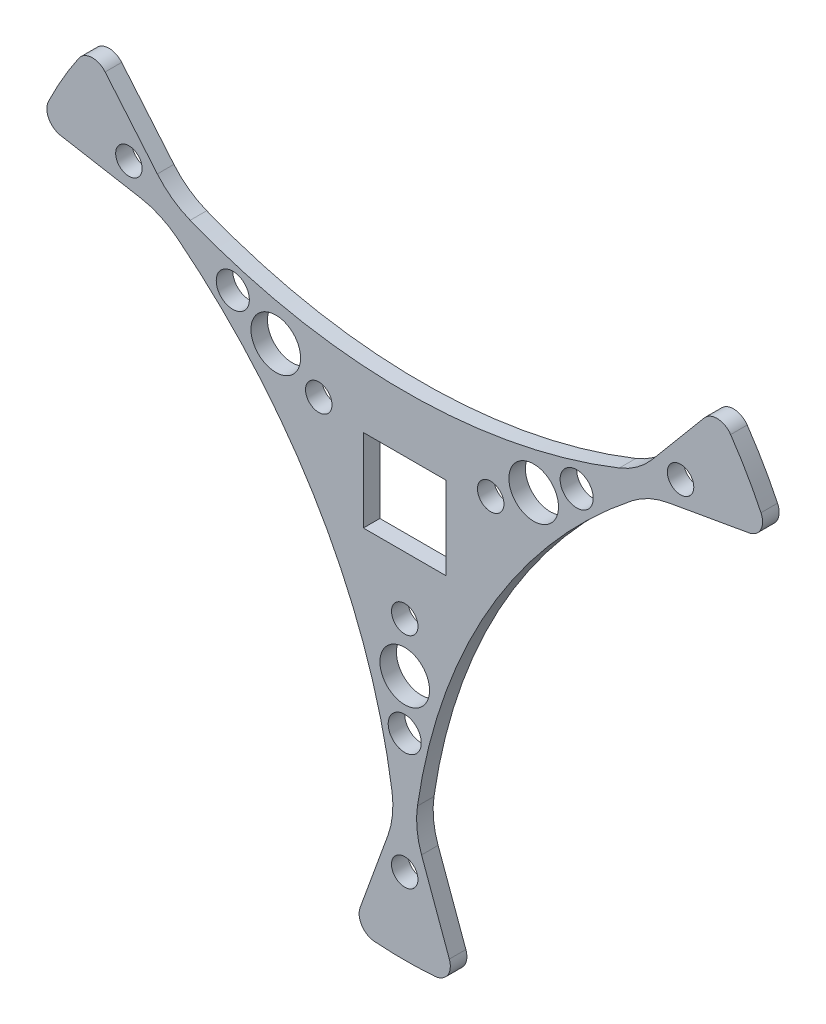
SolidWorks part; units mm, degrees
material "Thornel Mat VMA"
ref_plane "正面" through (0, 0, 0) normal (0, 0, 1) x (1, 0, 0)
ref_plane "平面" through (0, 0, 0) normal (0, 1, 0) x (1, 0, 0)
ref_plane "右側面" through (0, 0, 0) normal (1, 0, 0) x (0, 0, -1)
sketch "ｽｹｯﾁ1" plane through (0, 0, 0) normal (0, 0, 1) x (1, 0, 0)
  circle A0 centre (0, 0) radius 47.75
  dimension "D1" = 95.5
extrude "ﾎﾞｽ - 押し出し1" add sketch "ｽｹｯﾁ1" along normal blind 2
sketch "ｽｹｯﾁ2" plane through (0, 0, 2) normal (0, 0, 1) x (1, 0, 0)
  line L0 (-10.3, 46.6259) -> (-10.3, 31.8257) construction
  line L1 (10.3, 46.6259) -> (10.3, 31.8257) construction
  line L2 (0, 47.75) -> (0, -47.75) construction
  line L8 (22.0803, 42.3382) -> (12.5669, 31.0006) construction
  line L9 (37.8608, 29.0968) -> (28.3474, 17.7592) construction
  line L13 (0, 30.78) -> (0, 41.18) construction
  line L94 (44.1289, 18.24) -> (29.5536, 15.67) construction
  line L95 (47.7061, -2.047) -> (33.1308, -4.617) construction
  line L96 (45.5292, -14.3929) -> (32.7119, -6.9928) construction
  line L97 (35.2292, -32.233) -> (22.4119, -24.8329) construction
  line L98 (25.6258, -40.2912) -> (20.5639, -26.3836) construction
  line L99 (6.2682, -47.3368) -> (1.2062, -33.4292) construction
  line L100 (-6.2682, -47.3368) -> (-1.2062, -33.4292) construction
  line L101 (-25.6258, -40.2912) -> (-20.5639, -26.3836) construction
  line L102 (-35.2292, -32.233) -> (-22.4119, -24.8329) construction
  line L103 (-45.5292, -14.3929) -> (-32.7119, -6.9928) construction
  line L104 (-47.7061, -2.047) -> (-33.1308, -4.617) construction
  line L105 (-44.1289, 18.24) -> (-29.5536, 15.67) construction
  line L106 (-37.8608, 29.0968) -> (-28.3474, 17.7592) construction
  line L107 (-22.0803, 42.3382) -> (-12.5669, 31.0006) construction
  line L108 (-44.1289, 18.24) -> (-29.5536, 15.67)
  line L109 (-6.2682, -47.3368) -> (-1.2062, -33.4292)
  line L110 (6.2682, -47.3368) -> (1.2062, -33.4292)
  line L111 (29.5536, 15.67) -> (44.1289, 18.24)
  line L112 (-37.8608, 29.0968) -> (-28.3474, 17.7592)
  line L113 (28.3474, 17.7592) -> (37.8608, 29.0968)
  circle A0 centre (0, 0) radius 47.75 construction
  arc A1 (-10.3, 46.6259) -> (10.3, 46.6259) centre (0, 0) cw construction
  arc A2 (-10.3, 31.8257) -> (10.3, 31.8257) centre (0, 82.03) ccw construction
  arc A19 (12.5669, 31.0006) -> (28.3474, 17.7592) centre (52.7279, 62.8386) ccw construction
  arc A20 (22.0803, 42.3382) -> (37.8608, 29.0968) centre (0, 0) cw construction
  arc A21 (29.5536, 15.67) -> (33.1308, -4.617) centre (80.7838, 14.2444) ccw construction
  arc A22 (44.1289, 18.24) -> (47.7061, -2.047) centre (0, 0) cw construction
  arc A23 (32.7119, -6.9928) -> (22.4119, -24.8329) centre (71.0401, -41.015) ccw construction
  arc A24 (45.5292, -14.3929) -> (35.2292, -32.233) centre (0, 0) cw construction
  arc A25 (20.5639, -26.3836) -> (1.2062, -33.4292) centre (28.0559, -77.083) ccw construction
  arc A26 (25.6258, -40.2912) -> (6.2682, -47.3368) centre (0, 0) cw construction
  arc A27 (-1.2062, -33.4292) -> (-20.5639, -26.3836) centre (-28.0559, -77.083) ccw construction
  arc A28 (-6.2682, -47.3368) -> (-25.6258, -40.2912) centre (0, 0) cw construction
  arc A29 (-22.4119, -24.8329) -> (-32.7119, -6.9928) centre (-71.0401, -41.015) ccw construction
  arc A30 (-35.2292, -32.233) -> (-45.5292, -14.3929) centre (0, 0) cw construction
  arc A31 (-33.1308, -4.617) -> (-29.5536, 15.67) centre (-80.7838, 14.2444) ccw construction
  arc A32 (-47.7061, -2.047) -> (-44.1289, 18.24) centre (0, 0) cw construction
  arc A33 (-28.3474, 17.7592) -> (-12.5669, 31.0006) centre (-52.7279, 62.8386) ccw construction
  arc A34 (-37.8608, 29.0968) -> (-22.0803, 42.3382) centre (0, 0) cw construction
  arc A35 (-29.5536, 15.67) -> (-1.2062, -33.4292) centre (-71.0401, -41.015) cw
  arc A36 (1.2062, -33.4292) -> (29.5536, 15.67) centre (71.0401, -41.015) cw
  arc A37 (-44.1289, 18.24) -> (-6.2682, -47.3368) centre (0, 0) ccw
  arc A38 (6.2682, -47.3368) -> (44.1289, 18.24) centre (0, 0) ccw
  arc A39 (-28.3474, 17.7592) -> (28.3474, 17.7592) centre (0, 82.03) ccw
  arc A40 (-37.8608, 29.0968) -> (37.8608, 29.0968) centre (0, 0) cw
  circle A41 centre (0, -38.5) radius 1.6
  circle A42 centre (-33.342, 19.25) radius 1.6
  circle A44 centre (33.342, 19.25) radius 1.6
  point P11 (0, 41.18)
  point P56 (0, 0)
  point P67 (0, 0)
  point P139 (0, 0)
  dimension "D2" = 20.6
  dimension "D7" = 51.25
  dimension "D5" = 3.2
  dimension "D8" = 38.5
  dimension "D1" = 41.18
  dimension "D3" = 10.3
  dimension "D4" = 9
  dimension "D6" = 10.4
  dimension "D9" = 3
extrude "ｶｯﾄ - 押し出し1" cut sketch "ｽｹｯﾁ2" against normal through all
fillet "ﾌｨﾚｯﾄ1" radius 10 6 edges at (-1.2062, -33.4292, 1) (1.2062, -33.4292, 1) (29.5536, 15.67, 1) (28.3474, 17.7592, 1) (-28.3474, 17.7592, 1) (-29.5536, 15.67, 1)
sketch "ｽｹｯﾁ3" plane through (0, 0, 0) normal (0, 0, -1) x (-1, 0, 0)
  line L0 (0, 0) -> (0, -12) construction
  line L1 (5, -5) -> (-5, -5)
  line L2 (5, -5) -> (5, 5)
  line L3 (5, 5) -> (-5, 5)
  line L4 (-5, -5) -> (-5, 5)
  line L5 (5, -5) -> (-5, 5) construction
  line L6 (5, 5) -> (-5, -5) construction
  line L7 (-10.3923, 6) -> (0, 0) construction
  line L8 (0, 0) -> (10.3923, 6) construction
  line L9 (0, -12) -> (0, -47.75) construction
  line L10 (-10.3923, 6) -> (-41.3527, 23.875) construction
  line L11 (10.3923, 6) -> (41.3527, 23.875) construction
  circle A0 centre (-10.3923, 6) radius 1.6
  circle A1 centre (0, -12) radius 1.6
  circle A2 centre (10.3923, 6) radius 1.6
  arc A3 (-6.2682, -47.3368) -> (6.2682, -47.3368) centre (0, 0) ccw construction
  circle A4 centre (0, -18) radius 3
  circle A5 centre (0, -24) radius 2
  circle A6 centre (-15.5885, 9) radius 3
  circle A7 centre (-20.7846, 12) radius 2
  circle A8 centre (15.5885, 9) radius 3
  circle A9 centre (20.7846, 12) radius 2
  point P0 (0, 0)
  point P36 (0, 0)
  dimension "D4" = 3.2
  dimension "D6" = 6
  dimension "D7" = 6
  dimension "D8" = 4
  dimension "D9" = 6
  dimension "D1" = 10
  dimension "D2" = 120
  dimension "D3" = 120
  dimension "D5" = 12
  dimension "D10" = 3
extrude "ｶｯﾄ - 押し出し2" cut sketch "ｽｹｯﾁ3" against normal through all
fillet "ﾌｨﾚｯﾄ2" radius 2 6 edges at (-6.2682, -47.3368, 1) (6.2682, -47.3368, 1) (44.1289, 18.24, 1) (37.8608, 29.0968, 1) (-37.8608, 29.0968, 1) (-44.1289, 18.24, 1)
